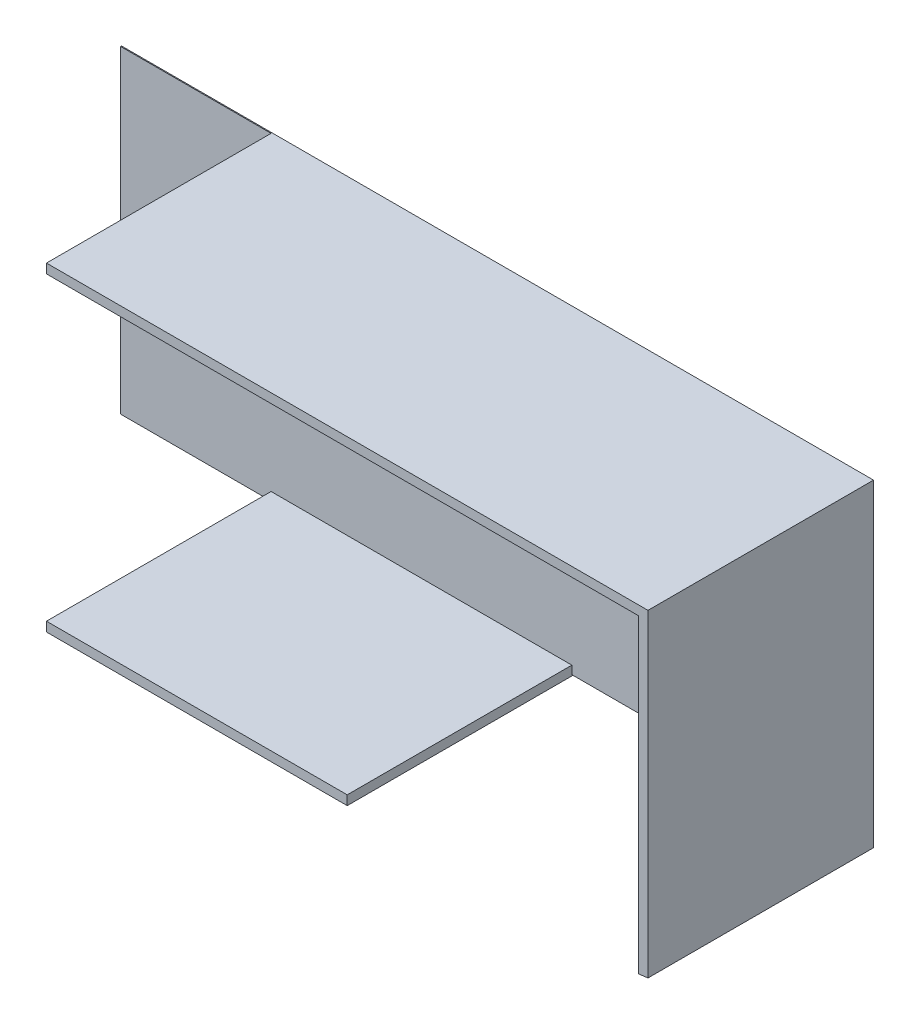
SolidWorks part; units mm, degrees
ref_plane "Front Plane" through (0, 0, 0) normal (0, 0, 1) x (1, 0, 0)
ref_plane "Top Plane" through (0, 0, 0) normal (0, 1, 0) x (1, 0, 0)
ref_plane "Right Plane" through (0, 0, 0) normal (1, 0, 0) x (0, 0, -1)
sketch "Sketch1" plane through (0, 0, 0) normal (0, 0, 1) x (1, 0, 0)
  line L0 (0, 0) -> (400.0965, 0)
  line L2 (0, 0) -> (0, 6.35)
  line L3 (0, 6.35) -> (406.4, 6.35)
  line L5 (0, -209.55) -> (203.2, -209.55)
  line L6 (0, -209.55) -> (0, -203.2)
  line L7 (0, -203.2) -> (203.2, -203.2)
  line L8 (203.2, -209.55) -> (203.2, -203.2)
  line L9 (400.0965, 0) -> (400.0965, -209.55)
  line L10 (400.0965, -209.55) -> (406.4, -208.7829)
  line L11 (406.4, -208.7829) -> (406.4, 6.35)
  line L12 (0, -203.2) -> (0, 0)
  line L13 (203.2, -209.55) -> (400.0965, -209.55)
  dimension "D1" = 406.4
  dimension "D2" = 6.35
  dimension "D3" = 6.35
  dimension "D4" = 203.2
  dimension "D5" = 0
  dimension "D6" = 6.35
  dimension "D7" = 203.2
extrude "Boss-Extrude1" add sketch "Sketch1" along normal blind 152.4 contours L10 L11 L3 L2 L0 L9 | L5 L8 L7 L6
sketch "Sketch3" plane through (0, 0, 0) normal (0, 0, -1) x (-1, 0, 0)
  line L4 (-406.4, -208.7829) -> (101.6, -208.7829)
  line L5 (101.6, -208.7829) -> (101.6, 6.35)
  line L6 (101.6, 6.35) -> (-406.4, 6.35)
  line L7 (-406.4, 6.35) -> (-406.4, -208.7829)
  dimension "D1" = 508
extrude "Boss-Extrude2" add sketch "Sketch3" against normal blind 0.635
